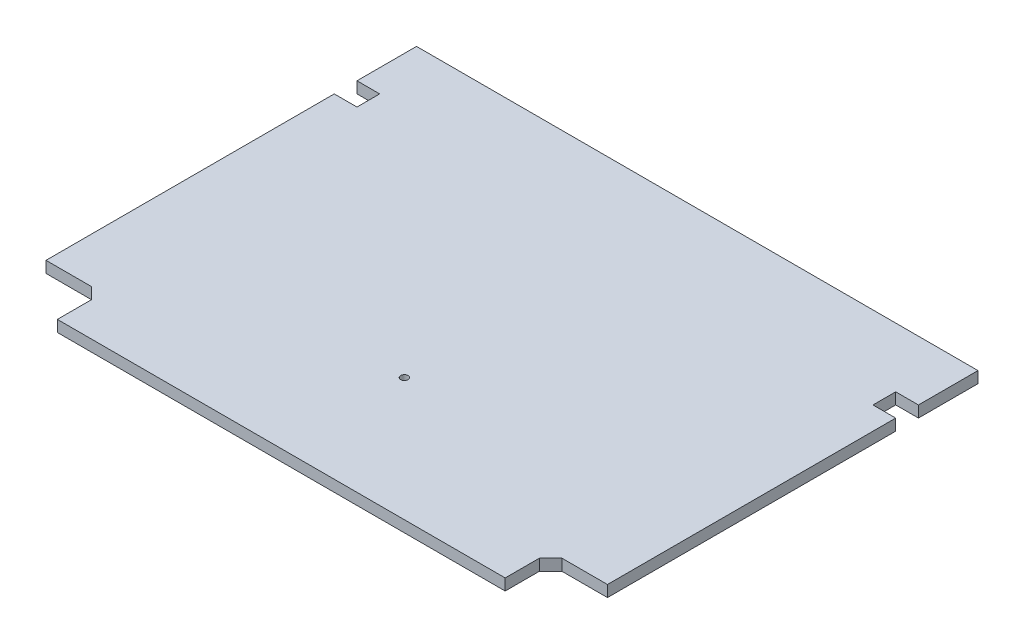
SolidWorks part; units mm, degrees
material "ABS PC"
ref_plane "Plan de face" through (0, 0, 0) normal (0, 0, 1) x (1, 0, 0)
ref_plane "Plan de dessus" through (0, 0, 0) normal (0, 1, 0) x (1, 0, 0)
ref_plane "Plan de droite" through (0, 0, 0) normal (1, 0, 0) x (0, 0, -1)
sketch "Esquisse1" plane through (0, 0, 0) normal (0, 1, 0) x (1, 0, 0)
  line L0 (-115.5, 5) -> (115.5, 5) construction
  line L1 (-123.5, 5) -> (123.5, 5)
  line L2 (-123.5, 23.2) -> (-123.5, -158) construction
  line L3 (-123.5, -31.2) -> (-123.5, -158)
  line L4 (123.5, 23.2) -> (123.5, -158) construction
  line L9 (123.5, -31.2) -> (123.5, -158)
  line L10 (-123.5, -158) -> (-103.5, -158)
  line L11 (-98.5, -163) -> (-98.5, -178)
  line L12 (-98.5, -178) -> (98.5, -178)
  line L13 (98.5, -178) -> (98.5, -163)
  line L14 (103.5, -158) -> (123.5, -158)
  line L15 (123.5, -31.2) -> (113.5, -31.2)
  line L16 (113.5, -31.2) -> (113.5, -21.2)
  line L17 (113.5, -21.2) -> (123.5, -21.2)
  line L18 (-123.5, -31.2) -> (-113.5, -31.2)
  line L19 (-113.5, -31.2) -> (-113.5, -21.2)
  line L20 (-113.5, -21.2) -> (-123.5, -21.2)
  line L21 (-123.5, -21.2) -> (-123.5, 5)
  line L22 (123.5, -21.2) -> (123.5, 5)
  line L23 (113.5, -31.2) -> (123.5, -31.2) construction
  line L24 (113.5, -21.2) -> (113.5, -31.2) construction
  line L25 (123.5, -21.2) -> (113.5, -21.2) construction
  line L26 (-113.5, -31.2) -> (-123.5, -31.2) construction
  line L27 (-113.5, -21.2) -> (-123.5, -21.2) construction
  line L28 (-113.5, -31.2) -> (-113.5, -21.2) construction
  line L29 (-115.5, -158) -> (115.5, -158) construction
  line L30 (-103.5, -158) -> (-98.5, -163)
  line L31 (98.5, -163) -> (103.5, -158)
  circle A1 centre (0, -123.86) radius 1.6 construction
  circle A2 centre (0, -123.86) radius 1.6
  point P11 (-98.5, -158)
  point P13 (98.5, -158)
  point P31 (96.1017, -178)
  dimension "D1" = 25
  dimension "D2" = 25
  dimension "D3" = 20
extrude "Boss.-Extru.1" add sketch "Esquisse1" along normal blind 5
